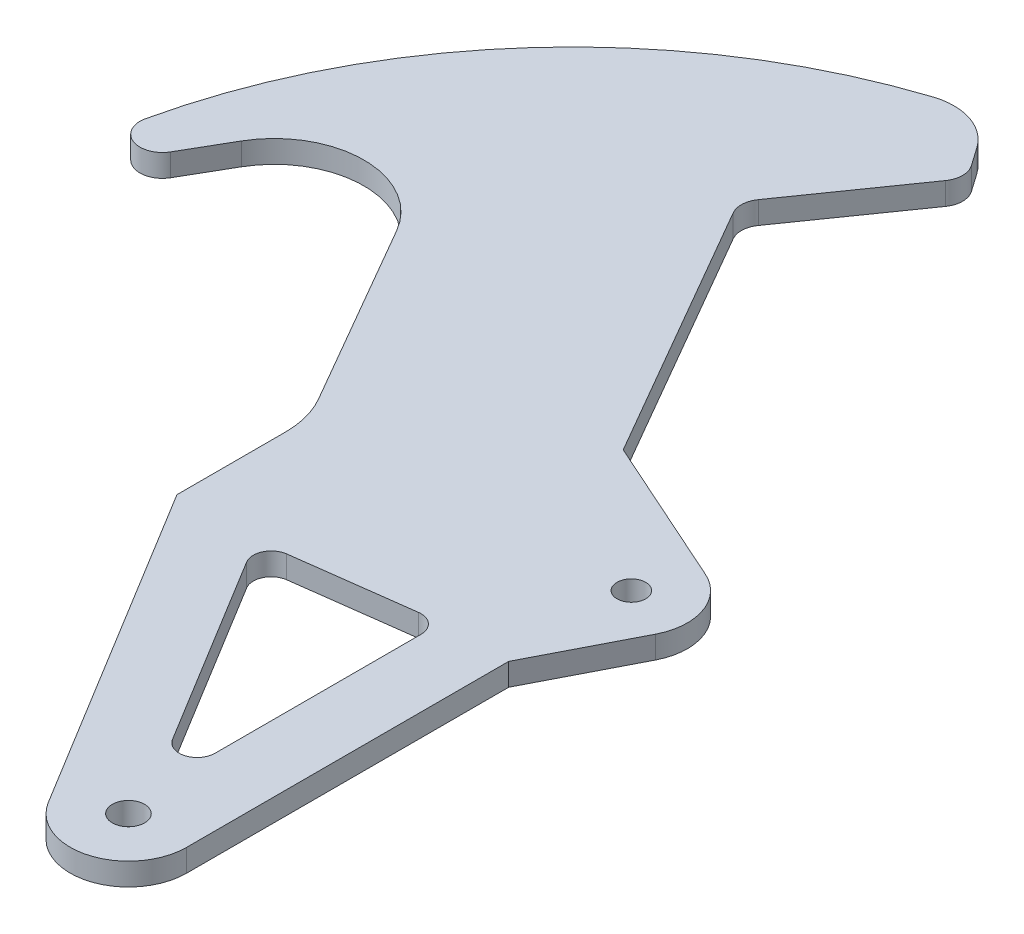
SolidWorks part; units mm, degrees
ref_plane "Front Plane" through (0, 0, 0) normal (0, 0, 1) x (1, 0, 0)
ref_plane "Top Plane" through (0, 0, 0) normal (0, 1, 0) x (1, 0, 0)
ref_plane "Right Plane" through (0, 0, 0) normal (1, 0, 0) x (0, 0, -1)
sketch "Sketch1" plane through (0, 0, 0) normal (0, 1, 0) x (1, 0, 0)
  line L2 (-10.9985, 23.8125) -> (-26.1215, -2.3813) construction
  line L3 (-15.123, -21.4313) -> (15.123, -21.4313) construction
  line L4 (26.1215, -2.3812) -> (10.9985, 23.8125) construction
  line L5 (-10.9985, 23.8125) -> (-14.6647, 17.4625)
  line L7 (41.9045, 75.0673) -> (43.7256, 72.4665)
  line L8 (10.9985, 23.8125) -> (26.1215, -2.3812)
  line L10 (71.755, -66.675) -> (71.755, -21.0815)
  line L11 (27.823, -8.7312) -> (27.823, -24.13)
  line L13 (-20.5141, 19.7372) -> (-18.41, 29.2281) construction
  line L14 (27.823, -24.13) -> (56.4564, -70.9799)
  line L15 (32.6501, 49.8109) -> (53.9226, 12.9658)
  line L16 (32.7989, 53.2195) -> (43.7256, 68.8243)
  line L17 (71.755, -21.0815) -> (78.815, -7.3415)
  line L18 (74.9982, 3.5308) -> (53.9226, 12.9658)
  circle A0 centre (0, 0) radius 21.4313 construction
  arc A1 (10.9985, 23.8125) -> (-10.9985, 23.8125) centre (0, 17.4625) ccw construction
  arc A2 (-26.1215, -2.3813) -> (-15.123, -21.4313) centre (-15.123, -8.7313) ccw construction
  arc A3 (15.123, -21.4313) -> (26.1215, -2.3812) centre (15.123, -8.7313) ccw construction
  arc A4 (-10.9985, 23.8125) -> (10.9985, 23.8125) centre (0, 17.4625) cw
  arc A5 (26.1215, -2.3812) -> (27.823, -8.7312) centre (15.123, -8.7312) cw
  arc A7 (41.9045, 75.0673) -> (32.5942, 78.1843) centre (35.1424, 70.3325) ccw
  arc A10 (-20.5141, 19.7372) -> (-14.6647, 17.4625) centre (-17.4143, 19.05) ccw
  arc A12 (-20.5141, 19.7372) -> (32.5942, 78.1843) centre (57.15, 2.5195) cw
  arc A13 (56.4564, -70.9799) -> (71.755, -66.675) centre (63.5, -66.675) ccw
  circle A14 centre (63.5, -66.675) radius 2.286
  arc A15 (32.7989, 53.2195) -> (32.6501, 49.8109) centre (35.3997, 51.3984) ccw
  arc A16 (43.7256, 68.8243) -> (43.7256, 72.4665) centre (41.1247, 70.6454) ccw
  arc A17 (78.815, -7.3415) -> (74.9982, 3.5308) centre (71.755, -3.7139) ccw
  circle A18 centre (71.755, -3.7139) radius 2.032
  dimension "D1" = 30.2459
  dimension "D2" = 12.7
  dimension "D3" = 57.15
  dimension "D4" = 6.35
  dimension "D5" = 8.255
  dimension "D6" = 19.05
  dimension "D8" = 4.572
  dimension "D7" = 17.5
  dimension "D11" = 80.9625
  dimension "D14" = 3.175
  dimension "D17" = 3.175
  dimension "D18" = 7.9375
  dimension "D19" = 63.5
  dimension "D23" = 4.064
  dimension "D9" = 66.675
  dimension "D10" = 42.545
  dimension "D12" = 63.5
  dimension "D13" = 145
  dimension "D15" = 19.05
  dimension "D16" = 3.175
  dimension "D20" = 31.75
  dimension "D21" = 42.545
  dimension "D22" = 8.255
  dimension "D24" = 115
extrude "Boss-Extrude1" add sketch "Sketch1" along normal blind 3.175
sketch "Sketch4" plane through (0, 3.175, 0) normal (0, 1, 0) x (1, 0, 0)
  line L11 (38.9861, -24.13) -> (62.23, -21.0815)
  line L12 (62.23, -21.0815) -> (62.23, -62.1617)
  line L13 (62.23, -62.1617) -> (38.9861, -24.13)
  line L14 (27.823, -24.13) -> (56.4564, -70.9799) construction
  line L16 (71.755, -66.675) -> (71.755, -21.0815) construction
  dimension "D1" = 9.525
  dimension "D6" = 9.525
extrude "Cut-Extrude2" cut sketch "Sketch4" against normal through all
fillet "Fillet1" [suppressed] radius 2.54
fillet "Fillet2" radius 2.54 3 edges at (62.23, 1.5875, 21.0815) (38.9861, 1.5875, 24.13) (62.23, 1.5875, 62.1617)
